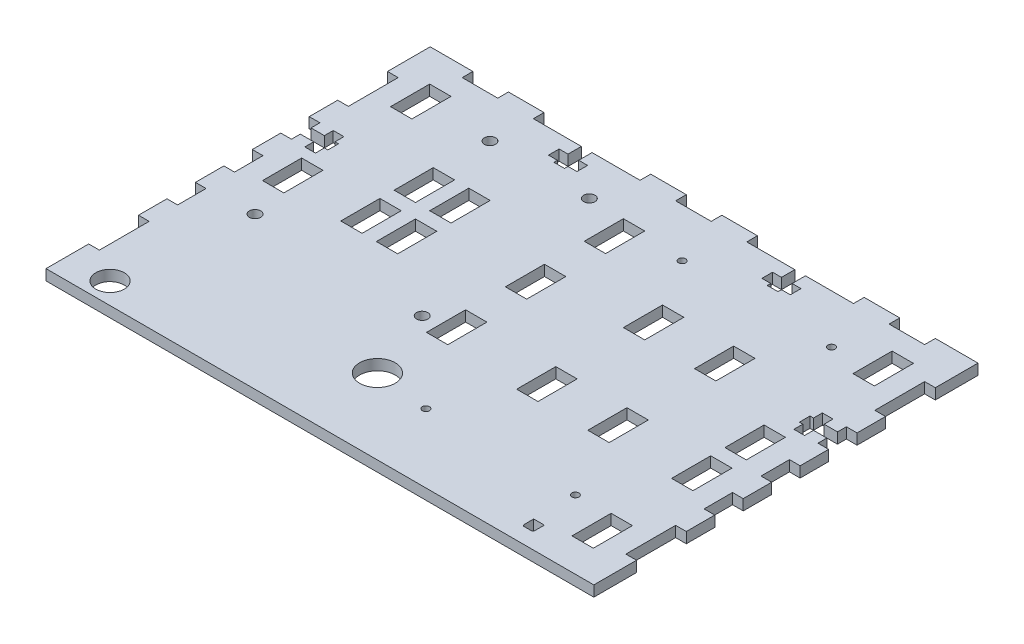
SolidWorks part; units mm, degrees
material "Balsa"
ref_plane "Alzado" through (0, 0, 0) normal (0, 0, 1) x (1, 0, 0)
ref_plane "Planta" through (0, 0, 0) normal (0, 1, 0) x (1, 0, 0)
ref_plane "Vista lateral" through (0, 0, 0) normal (1, 0, 0) x (0, 0, -1)
sketch "Croquis1" plane through (0, 0, 0) normal (0, 1, 0) x (1, 0, 0)
  line L0 (-77, 0) -> (-74, 0) construction
  line L1 (-77, -54) -> (77, -54)
  line L2 (-77, -54) -> (-77, 54)
  line L3 (-77, 54) -> (77, 54)
  line L4 (77, -54) -> (77, 54)
  line L5 (-77, -54) -> (77, 54) construction
  line L6 (-77, 54) -> (77, -54) construction
  line L7 (0, -54) -> (0, 54) construction
  line L8 (-74, 54) -> (-74, -54) construction
  line L9 (-77, -42) -> (-74, -42)
  line L10 (-77, 4) -> (-74, 4)
  line L11 (-77, 4) -> (-77, -4)
  line L12 (-77, -4) -> (-74, -4)
  line L13 (-74, 4) -> (-74, -4)
  line L14 (-77, 12) -> (-74, 12)
  line L15 (-77, 12) -> (-77, 20)
  line L16 (-77, 20) -> (-74, 20)
  line L17 (-74, 12) -> (-74, 20)
  line L22 (-77, 28) -> (-74, 28)
  line L23 (-77, 28) -> (-77, 42)
  line L24 (-77, 42) -> (-74, 42)
  line L25 (-74, 28) -> (-74, 42)
  line L26 (-74, -28) -> (-74, -42)
  line L27 (-77, -28) -> (-74, -28)
  line L28 (-77, -28) -> (-77, -42)
  line L29 (-77, -20) -> (-74, -20)
  line L30 (-74, -12) -> (-74, -20)
  line L31 (-77, -12) -> (-74, -12)
  line L32 (-77, -12) -> (-77, -20)
  line L33 (77, 42) -> (74, 42)
  line L34 (74, 28) -> (74, 42)
  line L35 (77, 28) -> (74, 28)
  line L36 (77, 28) -> (77, 42)
  line L37 (77, -28) -> (77, -42)
  line L38 (77, -28) -> (74, -28)
  line L39 (74, -28) -> (74, -42)
  line L40 (77, -42) -> (74, -42)
  line L41 (77, -12) -> (77, -20)
  line L42 (77, -12) -> (74, -12)
  line L43 (74, -12) -> (74, -20)
  line L44 (77, -20) -> (74, -20)
  line L45 (77, 20) -> (74, 20)
  line L46 (74, 12) -> (74, 20)
  line L47 (77, 12) -> (74, 12)
  line L48 (77, 12) -> (77, 20)
  line L49 (77, -4) -> (74, -4)
  line L50 (74, 4) -> (74, -4)
  line L51 (77, 4) -> (74, 4)
  line L52 (77, 4) -> (77, -4)
  line L53 (-77, 51) -> (77, 51) construction
  line L54 (-55, 51) -> (-65, 51)
  line L55 (-5, 54) -> (5, 54)
  line L56 (-5, 54) -> (-5, 51)
  line L57 (-5, 51) -> (5, 51)
  line L58 (5, 54) -> (5, 51)
  line L59 (15, 54) -> (45, 54)
  line L60 (15, 54) -> (15, 51)
  line L61 (15, 51) -> (45, 51)
  line L62 (45, 54) -> (45, 51)
  line L63 (55, 54) -> (65, 54)
  line L64 (55, 54) -> (55, 51)
  line L65 (55, 51) -> (65, 51)
  line L66 (65, 54) -> (65, 51)
  line L67 (-65, 54) -> (-65, 51)
  line L68 (-55, 54) -> (-65, 54)
  line L69 (-55, 54) -> (-55, 51)
  line L70 (-15, 51) -> (-45, 51)
  line L71 (-45, 54) -> (-45, 51)
  line L72 (-15, 54) -> (-45, 54)
  line L73 (-15, 54) -> (-15, 51)
  line L74 (-77, -48) -> (77, -48) construction
  line L75 (-30, 51) -> (-30, 10.4132) construction
  line L76 (53, -49.6) -> (55, -49.6)
  line L77 (52.5, -49.1) -> (52.5, -46.4)
  line L78 (52.5, -46.4) -> (55.5, -46.4)
  line L79 (55.5, -49.1) -> (55.5, -46.4)
  line L80 (52.5, -49.6) -> (55.5, -46.4) construction
  line L81 (52.5, -46.4) -> (55.5, -49.6) construction
  line L83 (-74, 1.5) -> (-74, -1.5)
  line L90 (-31.5, 51) -> (-28.5, 51)
  line L91 (-31.5, 51) -> (-31.5, 43.27)
  line L92 (-31.5, 43.27) -> (-28.5, 43.27)
  line L93 (-28.5, 51) -> (-28.5, 43.27)
  line L94 (-34, 47.25) -> (-26, 47.25)
  line L95 (-34, 47.25) -> (-34, 44.25)
  line L96 (-34, 44.25) -> (-26, 44.25)
  line L97 (-26, 47.25) -> (-26, 44.25)
  line L98 (31.5, 43.27) -> (28.5, 43.27)
  line L99 (28.5, 51) -> (28.5, 43.27)
  line L100 (31.5, 51) -> (28.5, 51)
  line L101 (31.5, 51) -> (31.5, 43.27)
  line L102 (34, 44.25) -> (26, 44.25)
  line L103 (26, 47.25) -> (26, 44.25)
  line L104 (34, 47.25) -> (26, 47.25)
  line L105 (34, 47.25) -> (34, 44.25)
  line L109 (74, 1.5) -> (74, -1.5)
  line L114 (-74, 16) -> (74, 16) construction
  line L115 (70.25, 12) -> (67.25, 12)
  line L116 (-74, 14.5) -> (-66.27, 14.5)
  line L117 (-74, 14.5) -> (-74, 17.5)
  line L118 (-74, 17.5) -> (-66.27, 17.5)
  line L119 (-66.27, 14.5) -> (-66.27, 17.5)
  line L120 (-70.25, 20) -> (-67.25, 20)
  line L121 (-70.25, 20) -> (-70.25, 12)
  line L122 (-70.25, 12) -> (-67.25, 12)
  line L123 (-67.25, 20) -> (-67.25, 12)
  line L124 (67.25, 20) -> (67.25, 12)
  line L125 (70.25, 20) -> (67.25, 20)
  line L126 (70.25, 20) -> (70.25, 12)
  line L127 (74, 17.5) -> (66.27, 17.5)
  line L128 (66.27, 14.5) -> (66.27, 17.5)
  line L129 (74, 14.5) -> (66.27, 14.5)
  line L130 (74, 14.5) -> (74, 17.5)
  line L131 (74, 0) -> (77, 0) construction
  circle A0 centre (-65, -48) radius 4
  arc A1 (55.5, -49.1) -> (55, -49.6) centre (55, -49.1) cw
  arc A2 (53, -49.6) -> (52.5, -49.1) centre (53, -49.1) cw
  point P0 (0, 0)
  point P78 (54, -48)
  point P123 (-75.5, 4)
  dimension "D17" = 8
  dimension "D22" = 0.5
  dimension "D1" = 108
  dimension "D2" = 154
  dimension "D3" = 3
  dimension "D4" = 4
  dimension "D5" = 3
  dimension "D6" = 8
  dimension "D7" = 8
  dimension "D8" = 8
  dimension "D9" = 14
  dimension "D10" = 3
  dimension "D11" = 5
  dimension "D12" = 10
  dimension "D13" = 10
  dimension "D14" = 30
  dimension "D15" = 10
  dimension "D16" = 10
  dimension "D18" = 6
  dimension "D19" = 23
  dimension "D20" = 3.2
  dimension "D21" = 3
  dimension "D23" = 12
  dimension "D31" = 3
  dimension "D32" = 8
  dimension "D33" = 1.5
  dimension "D34" = 4
  dimension "D35" = 0.98
  dimension "D36" = 7.73
  dimension "D37" = 8
  dimension "D38" = 3
  dimension "D39" = 1.5
  dimension "D40" = 0.98
  dimension "D41" = 8
  dimension "D42" = 4
  dimension "D43" = 3
  dimension "D44" = 7.73
extrude "Saliente-Extruir1" add sketch "Croquis1" along normal mid plane 3
sketch "Croquis2" plane through (0, 1.5, 0) normal (0, 1, 0) x (1, 0, 0)
  line L0 (-77, -12) -> (-77, -4) construction
  line L13 (-37.16, 10.02) -> (-31.16, 10.02)
  line L14 (-37.16, 10.02) -> (-37.16, -0.98)
  line L15 (-37.16, -0.98) -> (-31.16, -0.98)
  line L16 (-31.16, 10.02) -> (-31.16, -0.98)
  line L17 (-77, -54) -> (77, -54) construction
  line L18 (-15, 54) -> (-5, 54) construction
  line L19 (-8, 39.31) -> (-2, 39.31)
  line L20 (-8, 39.31) -> (-8, 28.31)
  line L21 (-8, 28.31) -> (-2, 28.31)
  line L22 (-2, 39.31) -> (-2, 28.31)
  line L23 (-47.16, 10.02) -> (-47.16, -0.98)
  line L24 (-47.16, 10.02) -> (-41.16, 10.02)
  line L25 (-41.16, 10.02) -> (-41.16, -0.98)
  line L26 (-47.16, -0.98) -> (-41.16, -0.98)
  line L27 (-47.16, 25.02) -> (-47.16, 14.02)
  line L28 (-47.16, 25.02) -> (-41.16, 25.02)
  line L29 (-41.16, 25.02) -> (-41.16, 14.02)
  line L30 (-47.16, 14.02) -> (-41.16, 14.02)
  line L31 (-37.16, 25.02) -> (-37.16, 14.02)
  line L32 (-37.16, 25.02) -> (-31.16, 25.02)
  line L33 (-31.16, 25.02) -> (-31.16, 14.02)
  line L34 (-37.16, 14.02) -> (-31.16, 14.02)
  line L35 (-8, 17.13) -> (-8, 6.13)
  line L36 (-8, 17.13) -> (-2, 17.13)
  line L37 (-2, 17.13) -> (-2, 6.13)
  line L38 (-8, 6.13) -> (-2, 6.13)
  line L39 (-8, -5.05) -> (-8, -16.05)
  line L40 (-8, -5.05) -> (-2, -5.05)
  line L41 (-2, -5.05) -> (-2, -16.05)
  line L42 (-8, -16.05) -> (-2, -16.05)
  line L43 (-5, -5.05) -> (-5, -32.83) construction
  line L44 (-77, 20) -> (-77, 28) construction
  line L45 (5, 54) -> (15, 54) construction
  line L46 (18.51, 23.8) -> (24.51, 23.8)
  line L47 (18.51, 23.8) -> (18.51, 12.8)
  line L48 (18.51, 12.8) -> (24.51, 12.8)
  line L49 (24.51, 23.8) -> (24.51, 12.8)
  line L50 (38.51, 23.8) -> (38.51, 12.8)
  line L51 (38.51, 23.8) -> (44.51, 23.8)
  line L52 (44.51, 23.8) -> (44.51, 12.8)
  line L53 (38.51, 12.8) -> (44.51, 12.8)
  line L54 (38.51, -6.2) -> (38.51, -17.2)
  line L55 (38.51, -6.2) -> (44.51, -6.2)
  line L56 (44.51, -6.2) -> (44.51, -17.2)
  line L57 (38.51, -17.2) -> (44.51, -17.2)
  line L58 (18.51, -6.2) -> (18.51, -17.2)
  line L59 (18.51, -6.2) -> (24.51, -6.2)
  line L60 (24.51, -6.2) -> (24.51, -17.2)
  line L61 (18.51, -17.2) -> (24.51, -17.2)
  line L62 (77, 42) -> (77, 54) construction
  line L63 (62, 44.86) -> (68, 44.86)
  line L64 (62, 44.86) -> (62, 33.86)
  line L65 (62, 33.86) -> (68, 33.86)
  line L66 (68, 44.86) -> (68, 33.86)
  line L67 (65, 54) -> (77, 54) construction
  line L72 (62, -6.14) -> (62, -17.14)
  line L73 (62, -17.14) -> (68, -17.14)
  line L74 (68, -6.14) -> (68, -17.14)
  line L75 (62, -6.14) -> (68, -6.14)
  line L76 (62, -34.14) -> (62, -45.14)
  line L77 (62, -45.14) -> (68, -45.14)
  line L78 (68, -34.14) -> (68, -45.14)
  line L79 (62, -34.14) -> (68, -34.14)
  line L80 (62, 8.86) -> (62, -2.14)
  line L81 (62, 8.86) -> (68, 8.86)
  line L82 (68, 8.86) -> (68, -2.14)
  line L83 (62, -2.14) -> (68, -2.14)
  line L84 (0, 0) -> (0, -8.6841) construction
  line L89 (-62, 8.86) -> (-68, 8.86)
  line L90 (-68, 8.86) -> (-68, -2.14)
  line L91 (-62, -2.14) -> (-68, -2.14)
  line L92 (-62, 8.86) -> (-62, -2.14)
  line L93 (-62, 33.86) -> (-68, 33.86)
  line L94 (-68, 44.86) -> (-68, 33.86)
  line L95 (-62, 44.86) -> (-68, 44.86)
  line L96 (-62, 44.86) -> (-62, 33.86)
  circle A0 centre (-5, -32.83) radius 5
  circle A1 centre (10.51, 37.3) radius 1
  circle A2 centre (52.51, 37.3) radius 1
  circle A3 centre (52.51, -34.7) radius 1
  circle A4 centre (10.51, -34.7) radius 1
  dimension "D10" = 10
  dimension "D26" = 2
  dimension "D1" = 45.84
  dimension "D2" = 11
  dimension "D3" = 6
  dimension "D4" = 53.02
  dimension "D5" = 2
  dimension "D6" = 2
  dimension "D7" = 3
  dimension "D8" = 4
  dimension "D9" = 4
  dimension "D11" = 16.78
  dimension "D12" = 69
  dimension "D13" = 11.18
  dimension "D14" = 11
  dimension "D15" = 11
  dimension "D16" = 6
  dimension "D17" = 14.69
  dimension "D18" = 6
  dimension "D19" = 8
  dimension "D20" = 30.2
  dimension "D23" = 19
  dimension "D24" = 14
  dimension "D25" = 8
  dimension "D27" = 16.7
  dimension "D28" = 87.51
  dimension "D31" = 42
  dimension "D32" = 72
  dimension "D33" = 8
  dimension "D34" = 6
  dimension "D35" = 11
  dimension "D36" = 9
  dimension "D37" = 9.14
  dimension "D21" = 2
  dimension "D22" = 2
  dimension "D29" = 2
  dimension "D30" = 2
  dimension "D40" = 2
  dimension "D38" = 2
extrude "Cortar-Extruir1" cut sketch "Croquis2" against normal blind 3
sketch "Croquis3" plane through (0, 1.5, 0) normal (0, 1, 0) x (1, 0, 0)
  line L0 (-55, 54) -> (-45, 54) construction
  line L1 (-77, 42) -> (-77, 54) construction
  line L2 (-77, -12) -> (-77, -4) construction
  circle A0 centre (-60.8889, -11.3481) radius 1.5875
  circle A1 centre (-12.6289, -12.6181) radius 1.5875
  circle A2 centre (-45.6489, 39.4519) radius 1.5875
  circle A3 centre (-17.7089, 39.4519) radius 1.5905
  dimension "D1" = 48.26
  dimension "D2" = 50.8
  dimension "D3" = 52.07
  dimension "D4" = 27.94
  dimension "D5" = 14.5481
  dimension "D6" = 31.3511
  dimension "D7" = 16.1111
extrude "Cortar-Extruir2" cut sketch "Croquis3" against normal blind 23
